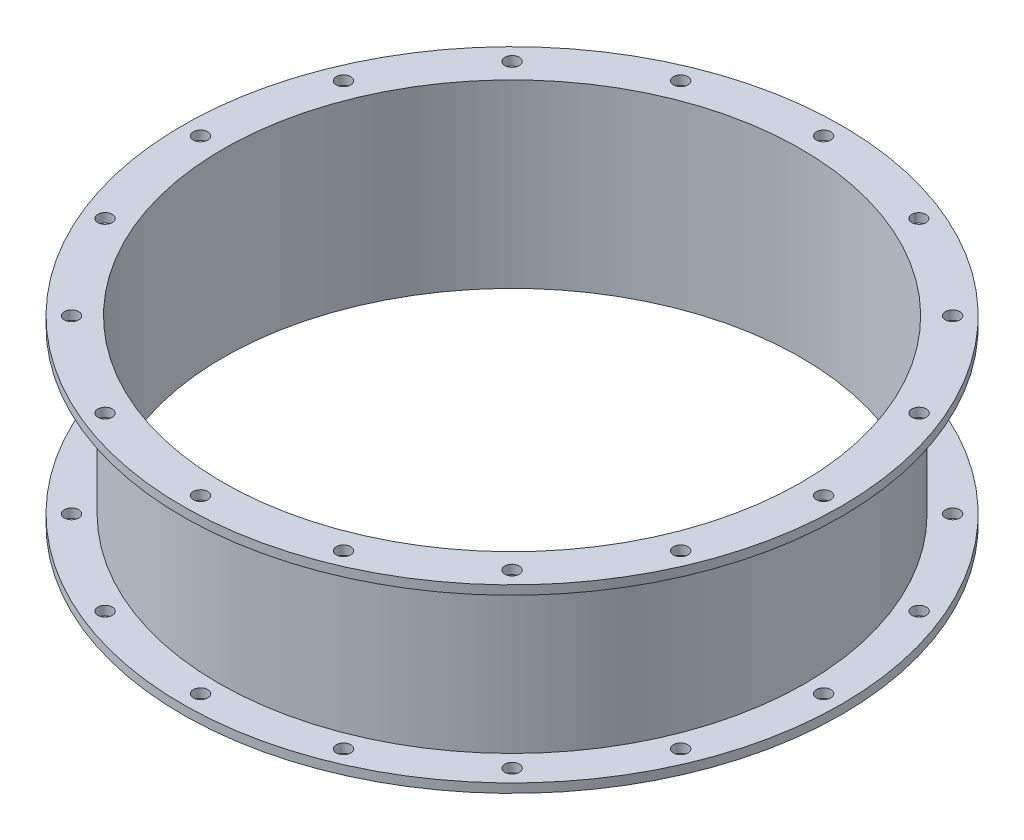
SolidWorks part; units mm, degrees
ref_plane "Front Plane" through (0, 0, 0) normal (0, 0, 1) x (1, 0, 0)
ref_plane "Top Plane" through (0, 0, 0) normal (0, 1, 0) x (1, 0, 0)
ref_plane "Right Plane" through (0, 0, 0) normal (1, 0, 0) x (0, 0, -1)
sketch "Sketch1" plane through (0, 0, 0) normal (0, 0, 1) x (1, 0, 0)
  line L0 (0, -8382.8405) -> (0, 410759.1858) construction
  line L12 (-320, 586.8186) -> (-320, 786.8186)
  line L15 (-325, 776.8186) -> (-325, 596.8186)
  line L16 (-365, 586.8186) -> (-365, 596.8186)
  line L17 (-365, 596.8186) -> (-325, 596.8186)
  line L18 (-365, 586.8186) -> (-320, 586.8186)
  line L19 (-1320, 686.8186) -> (48680, 686.8186) construction
  line L20 (-365, 776.8186) -> (-325, 776.8186)
  line L21 (-365, 786.8186) -> (-365, 776.8186)
  line L23 (-365, 786.8186) -> (-320, 786.8186)
  point P11 (-320, 686.8186)
  dimension "D1" = 200
  dimension "D2" = 640
  dimension "D3" = 10
  dimension "D4" = 45
revolve "Revolve1" add sketch "Sketch1" angle 360 about L0
sketch "Sketch2" plane through (0, 596.8186, 0) normal (0, 1, 0) x (1, 0, 0)
  line L0 (-1000, 0) -> (49000, 0) construction
  line L1 (0, -1000) -> (0, 49000) construction
  line L2 (-452.6973, -187.5134) -> (45741.2793, 18946.6582) construction
  line L3 (-452.6973, 187.5134) -> (45741.2793, -18946.6582) construction
  line L4 (0, 0) -> (19134.1716, 46193.9766) construction
  line L5 (0, 0) -> (-19134.1716, 46193.9766) construction
  line L6 (-707.1068, -707.1068) -> (34648.2323, 34648.2323) construction
  line L7 (707.1068, -707.1068) -> (-34648.2323, 34648.2323) construction
  circle A0 centre (0, 345) radius 8
  circle A1 centre (131.8905, 318.4118) radius 8
  circle A4 centre (132.0258, 318.7384) radius 8
  circle A5 centre (243.9518, 243.9518) radius 8
  circle A6 centre (318.7384, 132.0258) radius 8
  circle A7 centre (345, 0) radius 8
  circle A8 centre (318.7384, -132.0258) radius 8
  circle A9 centre (243.9518, -243.9518) radius 8
  circle A10 centre (132.0258, -318.7384) radius 8
  circle A11 centre (0, -345) radius 8
  circle A12 centre (-132.0258, -318.7384) radius 8
  circle A13 centre (-243.9518, -243.9518) radius 8
  circle A14 centre (-318.7384, -132.0258) radius 8
  circle A15 centre (-345, 0) radius 8
  circle A16 centre (-318.7384, 132.0258) radius 8
  circle A17 centre (-243.9518, 243.9518) radius 8
  circle A18 centre (-132.0258, 318.7384) radius 8
  point P55 (0, 0)
  dimension "D1" = 16
  dimension "D2" = 16
  dimension "D3" = 345
  dimension "D4" = 16
extrude "Cut-Extrude1" cut sketch "Sketch2" against normal through all both and the other way through all contours A12 | A13 | A5 | A1 A4 | A0 | A18 | A17 | A16 | A15 | A11 | A14 | A10 | A9 | A8 | A7 | A6
